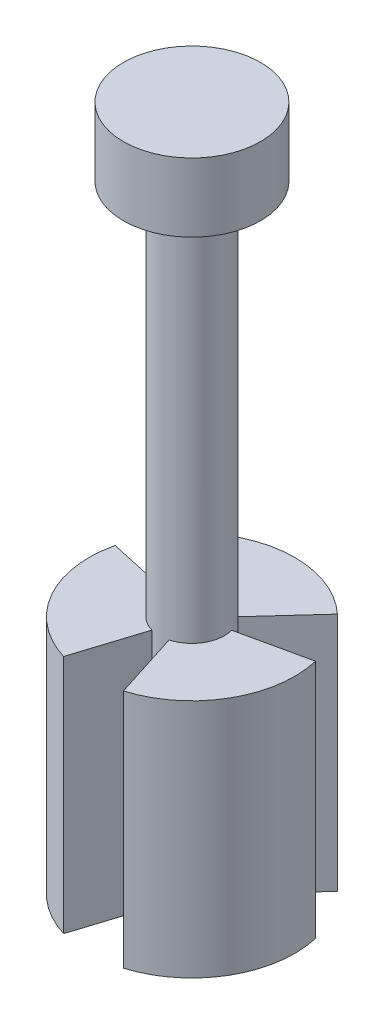
SolidWorks part; units mm, degrees
ref_plane "Front Plane" through (0, 0, 0) normal (0, 0, 1) x (1, 0, 0)
ref_plane "Top Plane" through (0, 0, 0) normal (0, 1, 0) x (1, 0, 0)
ref_plane "Right Plane" through (0, 0, 0) normal (1, 0, 0) x (0, 0, -1)
sketch "Sketch1" plane through (0, 0, 0) normal (0, 1, 0) x (1, 0, 0)
  circle A0 centre (0, 0) radius 0.95
  dimension "D1" = 1.9
extrude "Boss-Extrude1" add sketch "Sketch1" along normal blind 20 contours A0
sketch "Sketch2" plane through (0, 0, 0) normal (0, -1, 0) x (1, 0, 0)
  circle A0 centre (0, 0) radius 3
  circle A1 centre (0, 0) radius 0.95 construction
  circle A2 centre (0, 0) radius 0.95
  circle M2 centre (0, 0) radius 0.95
  dimension "D1" = 6
extrude "Boss-Extrude2" add sketch "Sketch2" against normal blind 7 contours A0 M2
sketch "Sketch3" plane through (0, 7, 0) normal (0, 1, 0) x (1, 0, 0)
  line L1 (0.25, -0.9165) -> (1.1585, -3.7756)
  line L2 (1.1585, -3.7756) -> (-1.1585, -3.7756)
  line L3 (-1.1585, -3.7756) -> (-0.25, -0.9165)
  line L5 (0, 0) -> (0, -3.7756) construction
  circle A2 centre (0, 0) radius 0.95 construction
  arc A4 (-0.25, -0.9165) -> (0.25, -0.9165) centre (0, 0) ccw
  dimension "D1" = 3
  dimension "D2" = 2.8591
  dimension "D3" = 0.5
extrude "Cut-Extrude1" cut sketch "Sketch3" against normal through all
pattern_circular "CirPattern1" count 3 over 360 about axis through (0, 0, 0) along (0, 1, 0) of "Cut-Extrude1"
ref_plane "Plane1" through (0, 18, 0) normal (0, 1, 0) x (1, 0, 0)
sketch "Sketch5" plane through (0, 18, 0) normal (0, 1, 0) x (1, 0, 0)
  circle A1 centre (0, 0) radius 2
  dimension "D1" = 4
extrude "Boss-Extrude3" add sketch "Sketch5" along normal up to surface (2 mm away) up to face at (0, 20, 0.95)
